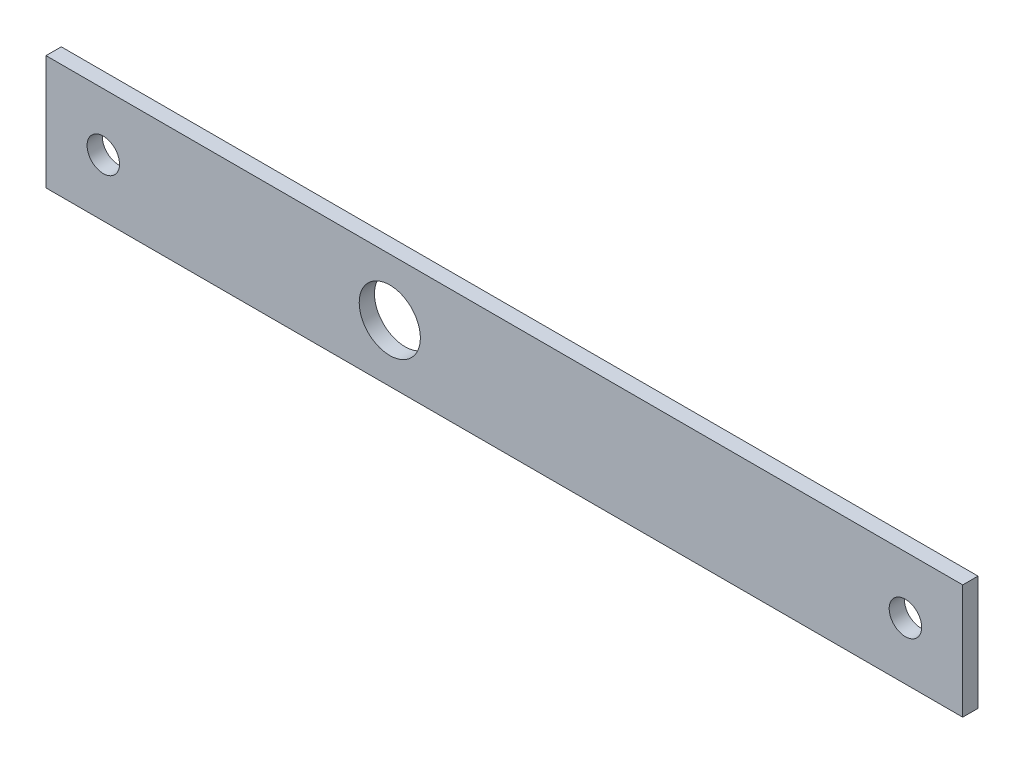
SolidWorks part; units mm, degrees
ref_plane "Front Plane" through (0, 0, 0) normal (0, 0, 1) x (1, 0, 0)
ref_plane "Top Plane" through (0, 0, 0) normal (0, 1, 0) x (1, 0, 0)
ref_plane "Right Plane" through (0, 0, 0) normal (1, 0, 0) x (0, 0, -1)
sketch "Sketch1" plane through (0, 0, 0) normal (0, 0, 1) x (1, 0, 0)
  line L1 (0, 0) -> (240, 0)
  line L2 (0, 0) -> (0, 30)
  line L3 (0, 30) -> (240, 30)
  line L4 (240, 0) -> (240, 30)
  dimension "D1" = 30
  dimension "D2" = 240
extrude "Boss-Extrude1" add sketch "Sketch1" along normal blind 4
sketch "Sketch2" plane through (0, 0, 4) normal (0, 0, 1) x (1, 0, 0)
  line L0 (240, 0) -> (240, 30) construction
  line L1 (0, 0) -> (240, 0) construction
  line L2 (240, 30) -> (0, 30) construction
  line L3 (0, 30) -> (0, 0) construction
  circle A0 centre (225, 15) radius 4.25
  circle A1 centre (15, 15) radius 4.25
  dimension "D1" = 8.5
  dimension "D2" = 8.5
  dimension "D3" = 15
  dimension "D4" = 15
  dimension "D5" = 15
  dimension "D6" = 15
extrude "Cut-Extrude1" cut sketch "Sketch2" against normal through all
sketch "Sketch3" plane through (0, 0, 0) normal (0, 0, -1) x (-1, 0, 0)
  line L0 (-240, 30) -> (0, 30) construction
  line L1 (-240, 0) -> (-240, 30) construction
  circle A0 centre (-90, 15) radius 8
  dimension "D2" = 150
  dimension "D3" = 16
  dimension "D1" = 15
extrude "Cut-Extrude2" cut sketch "Sketch3" against normal through all
